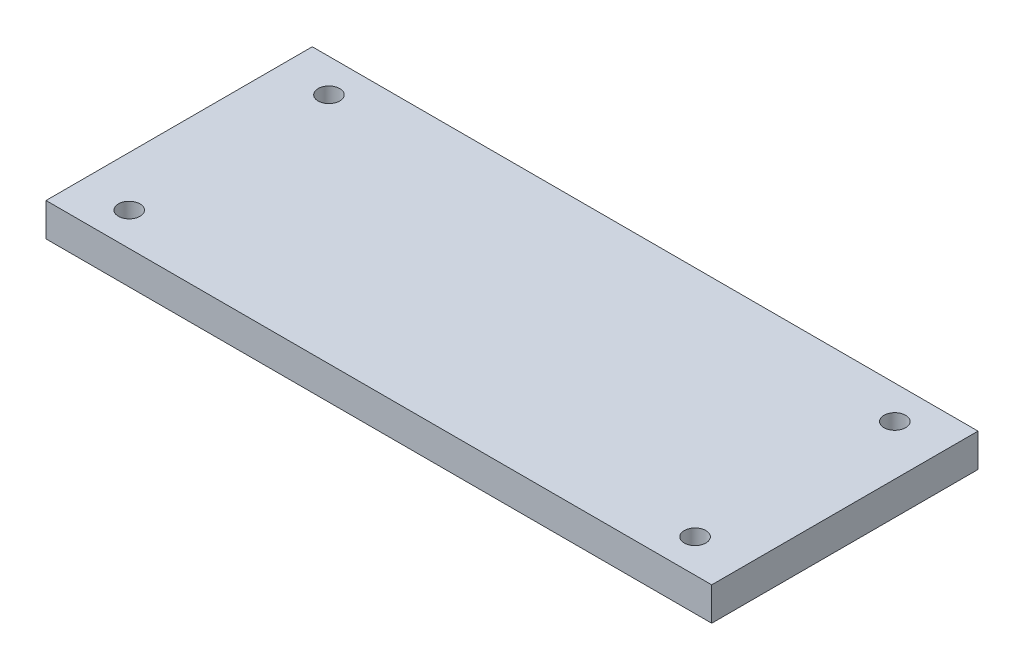
SolidWorks part; units mm, degrees
ref_plane "Front Plane" through (0, 0, 0) normal (0, 0, 1) x (1, 0, 0)
ref_plane "Top Plane" through (0, 0, 0) normal (0, 1, 0) x (1, 0, 0)
ref_plane "Right Plane" through (0, 0, 0) normal (1, 0, 0) x (0, 0, -1)
sketch "Sketch1" plane through (0, 0, 0) normal (0, 1, 0) x (1, 0, 0)
  line L0 (-62.1845, 40) -> (-62.1845, 30) construction
  line L1 (100, 40) -> (-100, 40)
  line L2 (100, 40) -> (100, -40)
  line L3 (100, -40) -> (-100, -40)
  line L4 (-100, 40) -> (-100, -40)
  line L5 (100, 40) -> (-100, -40) construction
  line L6 (100, -40) -> (-100, 40) construction
  point P0 (0, 0)
  dimension "D1" = 80
  dimension "D2" = 200
  dimension "D3" = 10
extrude "Boss-Extrude1" add sketch "Sketch1" along normal blind 10
sketch "Sketch2" plane through (0, 10, 0) normal (0, 1, 0) x (1, 0, 0)
  line L0 (0, 40) -> (0, -40) construction
  line L1 (100, 40) -> (-100, 40) construction
  line L2 (-100, -40) -> (100, -40) construction
  line L3 (-100, 0) -> (100, 0) construction
  line L4 (-100, 40) -> (-100, -40) construction
  line L5 (100, -40) -> (100, 40) construction
  circle A0 centre (-85, 30) radius 3.25
  circle A1 centre (85, 30) radius 3.25
  circle A2 centre (85, -30) radius 3.25
  circle A3 centre (-85, -30) radius 3.25
  dimension "D1" = 6.5
  dimension "D2" = 15
  dimension "D3" = 10
extrude "Cut-Extrude1" cut sketch "Sketch2" against normal through all
